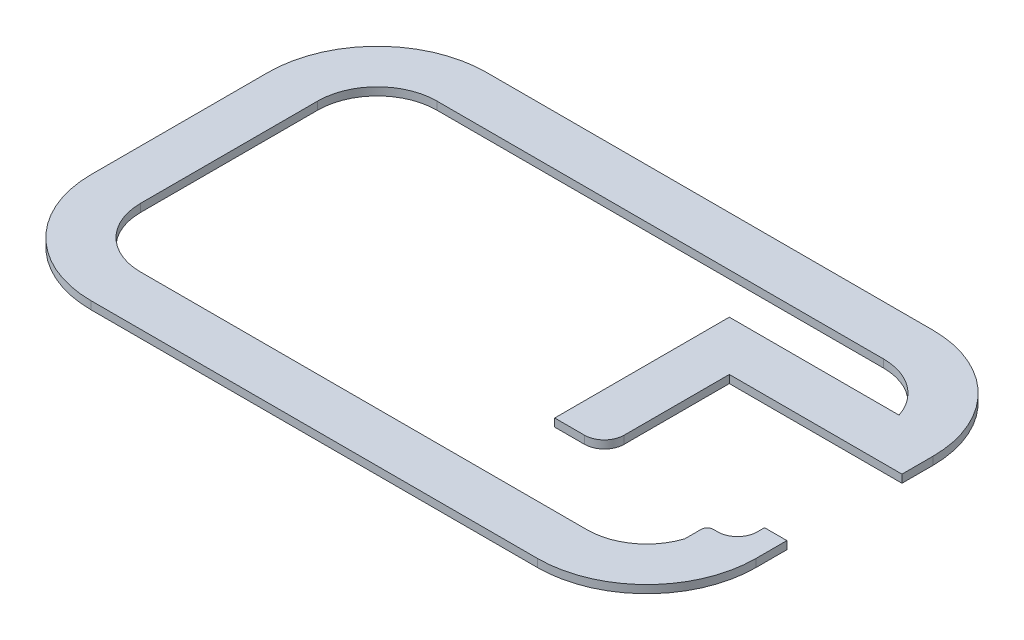
SolidWorks part; units mm, degrees
ref_plane "Front Plane" through (0, 0, 0) normal (0, 0, 1) x (1, 0, 0)
ref_plane "Top Plane" through (0, 0, 0) normal (0, 1, 0) x (1, 0, 0)
ref_plane "Right Plane" through (0, 0, 0) normal (1, 0, 0) x (0, 0, -1)
sketch "Sketch1" plane through (0, 0, 0) normal (0, 1, 0) x (1, 0, 0)
  line L0 (285.2957, -100.4595) -> (285.2957, -116.0895)
  line L1 (5.2657, 28.1705) -> (230.2957, 28.1705)
  line L2 (-49.7343, -26.8295) -> (-49.7343, -116.0895)
  line L3 (5.2657, -171.0895) -> (230.2957, -171.0895)
  line L4 (285.2957, -26.8295) -> (285.2957, -42.4595)
  line L5 (198.2957, -42.4595) -> (285.2957, -42.4595)
  line L6 (198.2957, -42.4595) -> (198.2957, -95.4595)
  line L7 (274.0453, -100.4595) -> (285.2957, -100.4595)
  line L8 (258.7949, -125.4595) -> (258.7949, -125.4595)
  line L9 (5.2657, -146.0895) -> (230.2957, -146.0895)
  line L10 (-24.7343, -26.8295) -> (-24.7343, -116.0895)
  line L11 (5.2657, 3.1705) -> (230.2957, 3.1705)
  line L12 (258.7949, -17.4595) -> (258.7949, -17.4595)
  line L13 (173.2957, -17.4595) -> (258.7949, -17.4595)
  line L14 (173.2957, -17.4595) -> (173.2957, -105.4595)
  line L15 (198.2957, -42.4595) -> (198.2957, -100.4595) construction
  line L16 (274.0453, -100.4595) -> (274.0453, -104.0895)
  line L17 (258.7949, -125.4595) -> (258.7949, -117.0895)
  line L18 (198.2957, -100.4595) -> (285.2957, -100.4595) construction
  line L19 (173.2957, -125.4595) -> (258.7949, -125.4595) construction
  line L20 (173.2957, -105.4595) -> (188.2957, -105.4595)
  line L21 (173.2957, -17.4595) -> (173.2957, -125.4595) construction
  line L22 (264.0453, -114.0895) -> (261.7949, -114.0895)
  arc A0 (5.2657, 28.1705) -> (-49.7343, -26.8295) centre (5.2657, -26.8295) ccw
  arc A1 (-49.7343, -116.0895) -> (5.2657, -171.0895) centre (5.2657, -116.0895) ccw
  arc A2 (230.2957, -171.0895) -> (285.2957, -116.0895) centre (230.2957, -116.0895) ccw
  arc A3 (230.2957, 28.1705) -> (285.2957, -26.8295) centre (230.2957, -26.8295) cw
  arc A4 (230.2957, -146.0895) -> (258.7949, -125.4595) centre (230.2957, -116.0895) ccw
  arc A5 (-24.7343, -116.0895) -> (5.2657, -146.0895) centre (5.2657, -116.0895) ccw
  arc A6 (5.2657, 3.1705) -> (-24.7343, -26.8295) centre (5.2657, -26.8295) ccw
  arc A7 (230.2957, 3.1705) -> (258.7949, -17.4595) centre (230.2957, -26.8295) cw
  arc A8 (198.2957, -95.4595) -> (188.2957, -105.4595) centre (188.2957, -95.4595) cw
  arc A9 (274.0453, -104.0895) -> (264.0453, -114.0895) centre (264.0453, -104.0895) cw
  arc A10 (261.7949, -114.0895) -> (258.7949, -117.0895) centre (261.7949, -117.0895) ccw
  point P6 (-49.7343, 28.1705)
  point P9 (-49.7343, -171.0895)
  point P14 (285.2957, 28.1705)
  dimension "D3" = 55
  dimension "D7" = 10
  dimension "D5" = 10
  dimension "D8" = 3
  dimension "D1" = 335.03
  dimension "D2" = 199.26
  dimension "D4" = 87
  dimension "D6" = 25
extrude "Boss-Extrude1" add sketch "Sketch1" along normal blind 4
